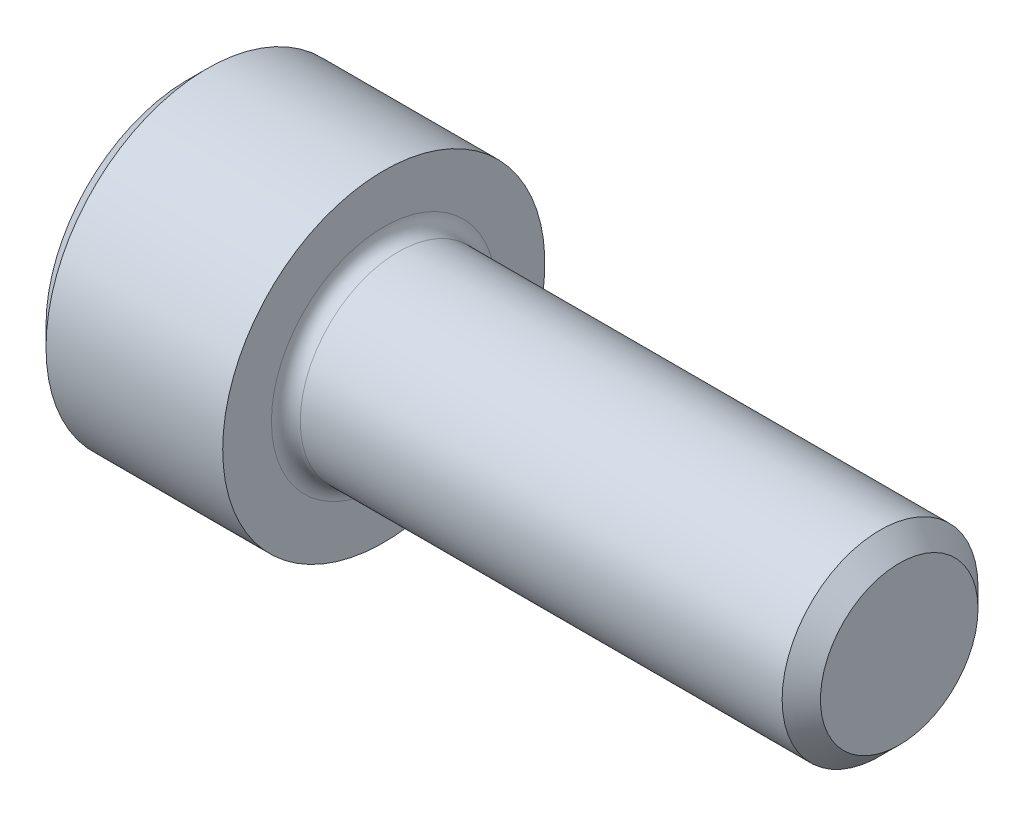
SolidWorks part; units mm, degrees
ref_plane "Front Plane" through (0, 0, 0) normal (0, 0, 1) x (1, 0, 0)
ref_plane "Top Plane" through (0, 0, 0) normal (0, 1, 0) x (1, 0, 0)
ref_plane "Right Plane" through (0, 0, 0) normal (1, 0, 0) x (0, 0, -1)
ref_plane "Plane1" through (0, 0, 0) normal (0, 0, -1) x (-1, 0, 0)
sketch "Sketch1" plane through (0, 0, 0) normal (0, 0, -1) x (-1, 0, 0)
  line L0 (-4.826, 3.9688) -> (-4.826, 0)
  line L1 (-4.826, 0) -> (0, 0)
  line L2 (0, 0) -> (0, 3.9688)
  line L3 (0, 3.9688) -> (-4.826, 3.9688)
  line L4 (-4.826, 0) -> (0, 0) construction
revolve "Revolve1" add sketch "Sketch1" angle 360 about L4
sketch "Sketch2" plane through (4.826, 0, 0) normal (1, 0, 0) x (0, 0, -1)
  circle A0 centre (0, 0) radius 2.413
extrude "Boss-Extrude1" add sketch "Sketch2" along normal blind 12.7
sketch "Sketch3" plane through (0, 0, 0) normal (-1, 0, 0) x (0, 0, 1)
  line L0 (0, -2.2921) -> (1.985, -1.146)
  line L1 (1.985, -1.146) -> (1.985, 1.146)
  line L2 (1.985, 1.146) -> (0, 2.2921)
  line L3 (0, 2.2921) -> (-1.985, 1.146)
  line L4 (-1.985, 1.146) -> (-1.985, -1.146)
  line L5 (-1.985, -1.146) -> (0, -2.2921)
extrude "Cut-Extrude1" cut sketch "Sketch3" against normal blind 2.286
sketch "Sketch4" plane through (0, 0, 0) normal (0, 0, 1) x (1, 0, 0)
  line L0 (2.286, 1.985) -> (2.286, 0)
  line L1 (2.286, 0) -> (3.432, 0)
  line L2 (3.432, 0) -> (2.286, 1.985)
  line L3 (2.286, 0) -> (3.432, 0) construction
revolve "Cut-Revolve1" cut sketch "Sketch4" angle 360 about L3
chamfer "Chamfer1" distance 0.4724 angle 45 2 edges at (0, 0, 3.9688) (17.526, 0, -2.413)
fillet "Fillet1" radius 0.3556 1 edges at (4.826, 0, -2.413)
